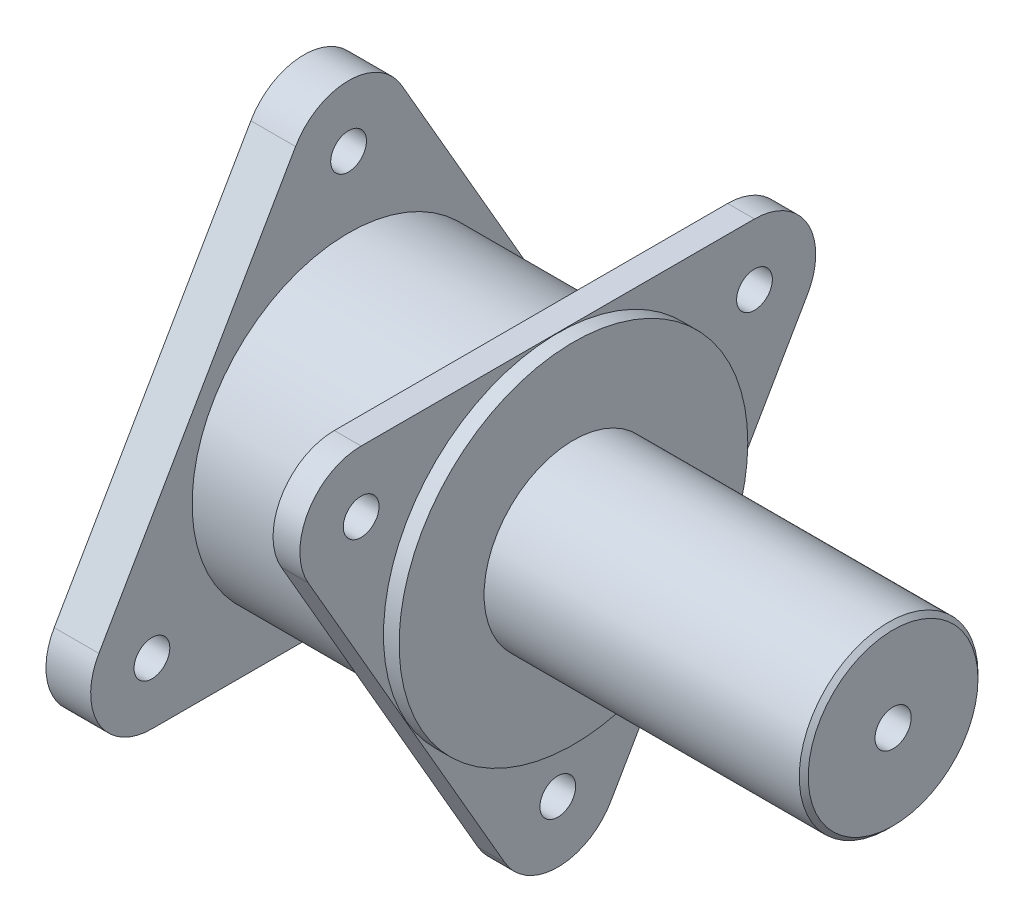
SolidWorks part; units mm, degrees
other "Markup1"
sketch "Sketch15" plane through (0, -64.5, 57.6941) normal (-0.9121, -0.2697, 0.3087) x (0.4098, -0.6172, 0.6716)
ref_plane "Front Plane" through (0, 0, 0) normal (0, 0, 1) x (1, 0, 0)
ref_plane "Top Plane" through (0, 0, 0) normal (0, 1, 0) x (1, 0, 0)
ref_plane "Right Plane" through (0, 0, 0) normal (1, 0, 0) x (0, 0, -1)
sketch "Sketch10" plane through (0, 0, 0) normal (1, 0, 0) x (0, 0, -1)
  line L0 (-55.8586, -18.55) -> (-11.8645, 57.65)
  line L1 (11.8645, 57.65) -> (55.8586, -18.55)
  line L2 (-43.9941, -39.1) -> (43.9941, -39.1)
  circle A0 centre (0, 0) radius 64.5 construction
  circle A1 centre (0, 0) radius 50.8 construction
  circle A2 centre (0, 50.8) radius 4
  circle A3 centre (43.9941, -25.4) radius 4
  circle A4 centre (-43.9941, -25.4) radius 4
  arc A5 (11.8645, 57.65) -> (-11.8645, 57.65) centre (0, 50.8) ccw
  arc A6 (43.9941, -39.1) -> (55.8586, -18.55) centre (43.9941, -25.4) ccw
  arc A7 (-55.8586, -18.55) -> (-43.9941, -39.1) centre (-43.9941, -25.4) ccw
  point P8 (-13.5749, 48.9527)
  point P12 (0, 0)
  point P13 (-49.1817, -12.7201)
  point P18 (0, 0)
  point P19 (13.5749, 48.9527)
  point P20 (49.1817, -12.7201)
  dimension "D1" = 129
  dimension "D2" = 101.6
  dimension "D3" = 8
  dimension "D7" = 27.4
  dimension "D5" = 76.2
  dimension "D6" = 43.9941
  dimension "D4" = 3
  dimension "D8" = 3
extrude "Boss-Extrude12" add sketch "Sketch10" along normal blind 10
sketch "Sketch11" plane through (10, 0, 0) normal (1, 0, 0) x (0, 0, -1)
  circle A0 centre (0, 0) radius 35
  dimension "D1" = 70
extrude "Boss-Extrude13" add sketch "Sketch11" along normal blind 40.8
sketch "Sketch12" plane through (50.8, 0, 0) normal (1, 0, 0) x (0, 0, -1)
  line L0 (-43.9941, 39.1) -> (43.9941, 39.1)
  line L1 (-55.8586, 18.55) -> (-11.8645, -57.65)
  line L2 (55.8586, 18.55) -> (11.8645, -57.65)
  circle A0 centre (0, 0) radius 50.8 construction
  circle A3 centre (43.9941, 25.4) radius 4
  circle A5 centre (0, -50.8) radius 4
  circle A7 centre (-43.9941, 25.4) radius 4
  arc A10 (-43.9941, 39.1) -> (-55.8586, 18.55) centre (-43.9941, 25.4) ccw
  arc A11 (55.8586, 18.55) -> (43.9941, 39.1) centre (43.9941, 25.4) ccw
  arc A12 (-11.8645, -57.65) -> (11.8645, -57.65) centre (0, -50.8) ccw
  point P15 (0, 0)
  point P19 (0, 0)
  dimension "D1" = 101.6
  dimension "D2" = 27.4
  dimension "D3" = 3
extrude "Boss-Extrude14" add sketch "Sketch12" along normal blind 6
sketch "Sketch13" plane through (56.8, 0, 0) normal (1, 0, 0) x (0, 0, -1)
  circle A0 centre (0, 0) radius 19.993
  dimension "D1" = 39.986
extrude "Boss-Extrude15" add sketch "Sketch13" along normal blind 75
sketch "Sketch16" plane through (56.8, 0, 0) normal (1, 0, 0) x (0, 0, -1)
  circle A0 centre (0, 0) radius 39
  dimension "D1" = 78
extrude "Boss-Extrude16" add sketch "Sketch16" along normal blind 3.5
chamfer "Chamfer1" distance 1 angle 45 1 edges at (131.8, 0, -19.993)
sketch "Sketch17" plane through (131.8, 0, 0) normal (1, 0, 0) x (0, 0, -1)
  circle A0 centre (0, 0) radius 4.05
  dimension "D1" = 8.1
extrude "Cut-Extrude1" cut sketch "Sketch17" against normal up to surface (131.8 mm away) up to face at (0, 0, 0)
